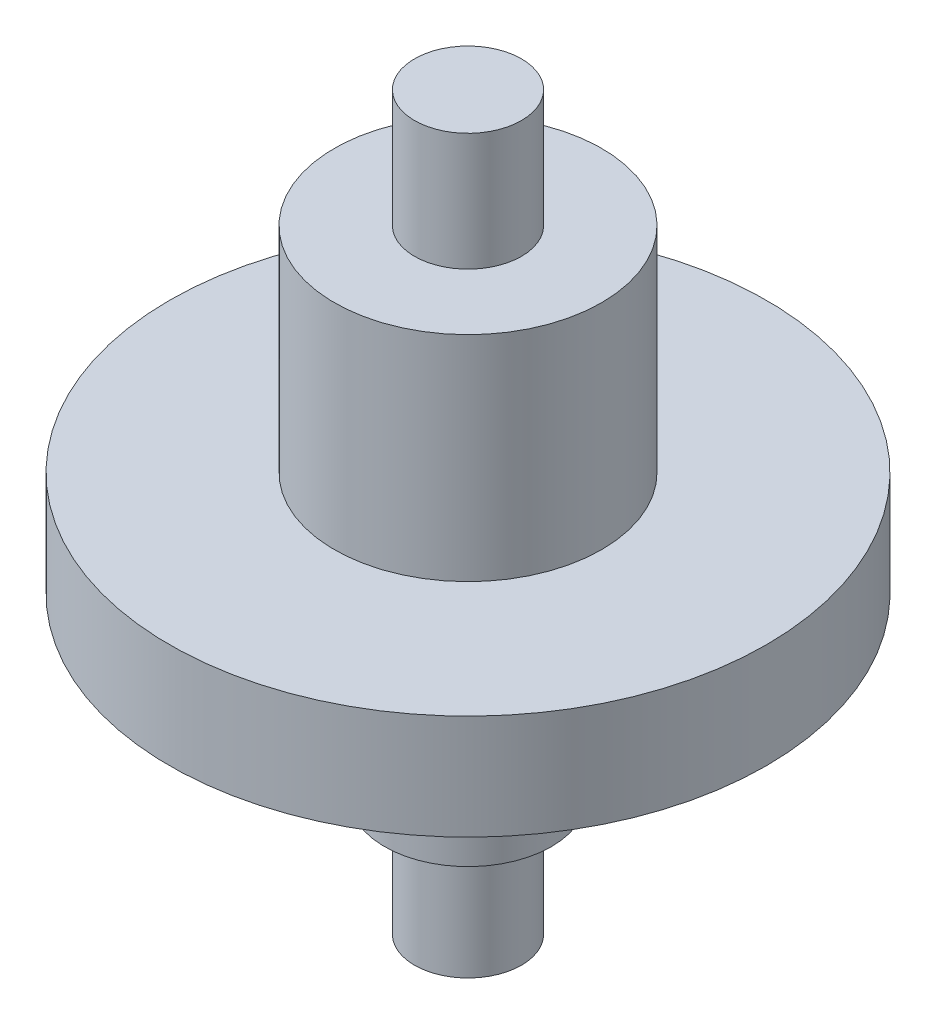
SolidWorks part; units mm, degrees
ref_plane "正面" through (0, 0, 0) normal (0, 0, 1) x (1, 0, 0)
ref_plane "平面" through (0, 0, 0) normal (0, 1, 0) x (1, 0, 0)
ref_plane "右側面" through (0, 0, 0) normal (1, 0, 0) x (0, 0, -1)
sketch "ｽｹｯﾁ1" plane through (0, 0, 0) normal (0, 0, 1) x (1, 0, 0)
  line L0 (0, 0) -> (0, 17.1)
  line L1 (0, 17.1) -> (1.25, 17.1)
  line L2 (1.25, 17.1) -> (1.25, 14.35)
  line L3 (1.25, 14.35) -> (3.125, 14.35)
  line L5 (6.975, 6.9) -> (1.95, 6.9)
  line L6 (1.95, 6.9) -> (1.95, 2.75)
  line L7 (1.95, 2.75) -> (1.25, 2.75)
  line L8 (1.25, 2.75) -> (1.25, 0)
  line L9 (1.25, 0) -> (0, 0)
  line L10 (3.125, 14.35) -> (3.125, 9.35)
  line L11 (3.125, 9.35) -> (6.975, 9.35)
  line L12 (6.975, 9.35) -> (6.975, 6.9)
  dimension "D1" = 4.15
  dimension "D2" = 1.25
  dimension "D3" = 2.75
  dimension "D4" = 2.75
  dimension "D5" = 5
  dimension "D6" = 2.45
  dimension "D7" = 3.125
  dimension "D8" = 6.975
  dimension "D9" = 1.95
  dimension "D10" = 17.1
revolve "回転1" add sketch "ｽｹｯﾁ1" angle 360 about L0
